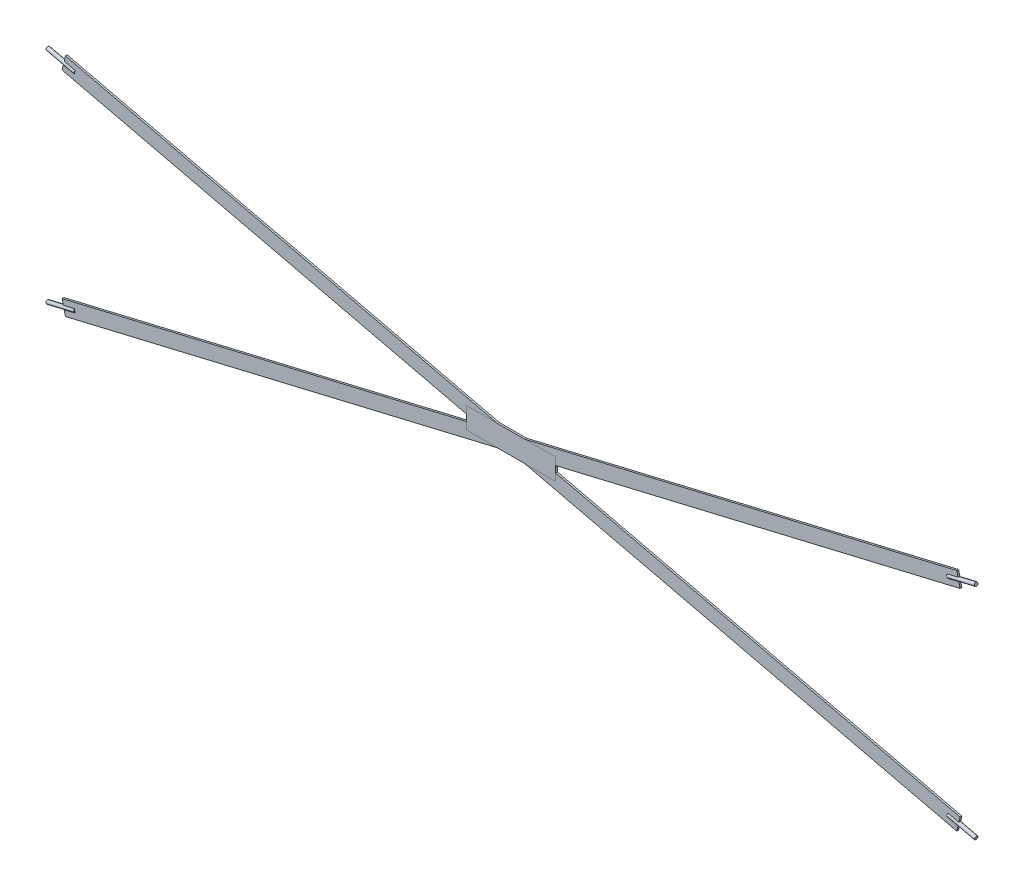
SolidWorks part; units mm, degrees
material "Plain Carbon Steel"
ref_plane "Front Plane" through (0, 0, 0) normal (0, 0, 1) x (1, 0, 0)
ref_plane "Top Plane" through (0, 0, 0) normal (0, 1, 0) x (1, 0, 0)
ref_plane "Right Plane" through (0, 0, 0) normal (1, 0, 0) x (0, 0, -1)
sketch "Sketch1" plane through (0, 0, 0) normal (0, 0, 1) x (1, 0, 0)
  line L0 (2522.0281, -597.1118) -> (-2522.0281, 597.1118)
  line L1 (-2522.0281, -597.1118) -> (2522.0281, 597.1118)
  line L2 (250, -59.1896) -> (-250, -59.1896)
  line L3 (250, -59.1896) -> (250, 59.1896)
  line L4 (250, 59.1896) -> (-250, 59.1896)
  line L5 (-250, -59.1896) -> (-250, 59.1896)
  line L6 (250, -59.1896) -> (-250, 59.1896) construction
  line L7 (250, 59.1896) -> (-250, -59.1896) construction
  line L8 (0, 0) -> (2683.4766, 0) construction
  point P2 (0, 0)
  point P5 (0, 0)
  dimension "D1" = 2591.75
  dimension "D2" = 2591.75
  dimension "D3" = 500
  dimension "D4" = 13.32
  dimension "D5" = 13.32
  dimension "D6" = 5183.5
  dimension "D7" = 5183.5
extrude "Boss-Extrude1" add sketch "Sketch1" along normal mid plane 10 contours L1 L4 L0 | L0 L3 L1 | L2 L0 L1 | L5 L1 L0
sketch "Sketch2" plane through (0, 0, 0) normal (0, 0, 1) x (1, 0, 0)
  line L0 (250, 18.0838) -> (250, 59.1896)
  line L1 (250, -59.1896) -> (250, 59.1896) construction
  line L2 (250, 59.1896) -> (76.3809, 59.1896)
  line L3 (250, 59.1896) -> (-250, 59.1896) construction
  line L4 (76.3809, 59.1896) -> (2496.4769, 632.1682)
  line L5 (250, 18.0838) -> (2514.9081, 554.3203)
  line L6 (-2522.0281, -597.1118) -> (2522.0281, 597.1118) construction
  line L7 (2514.9081, 554.3203) -> (2496.4769, 632.1682)
  line L8 (0, 59.1896) -> (0, 886.3837) construction
  line L9 (250, 59.1896) -> (-250, 59.1896) construction
  line L10 (-2514.9081, 554.3203) -> (-2496.4769, 632.1682)
  line L11 (-250, 18.0838) -> (-2514.9081, 554.3203)
  line L12 (-76.3809, 59.1896) -> (-2496.4769, 632.1682)
  line L13 (-250, 59.1896) -> (-76.3809, 59.1896)
  line L14 (-250, 18.0838) -> (-250, 59.1896)
  line L15 (11.5564, 0) -> (3168.9278, 0) construction
  line L16 (0, 0) -> (2683.4766, 0) construction
  line L17 (0, -59.1896) -> (0, -886.3837) construction
  line L18 (-250, -18.0838) -> (-250, -59.1896)
  line L19 (-250, -59.1896) -> (-76.3809, -59.1896)
  line L20 (-76.3809, -59.1896) -> (-2496.4769, -632.1682)
  line L21 (-250, -18.0838) -> (-2514.9081, -554.3203)
  line L22 (-2514.9081, -554.3203) -> (-2496.4769, -632.1682)
  line L23 (2514.9081, -554.3203) -> (2496.4769, -632.1682)
  line L24 (250, -18.0838) -> (2514.9081, -554.3203)
  line L25 (76.3809, -59.1896) -> (2496.4769, -632.1682)
  line L26 (250, -59.1896) -> (76.3809, -59.1896)
  line L27 (250, -18.0838) -> (250, -59.1896)
  point P17 (2505.6925, 593.2442)
  point P19 (-2505.6925, 593.2442)
  point P42 (-2505.6925, -593.2442)
  point P43 (2505.6925, -593.2442)
  dimension "D1" = 40
  dimension "D2" = 40
  dimension "D3" = 2487
extrude "Boss-Extrude2" add sketch "Sketch2" along normal mid plane 10 separate body
sketch "Sketch3" plane through (0, 0, 5) normal (0, 0, 1) x (1, 0, 0)
  line L0 (2602.1798, 605.812) -> (2446.4841, 568.9497)
  line L1 (2602.1798, 605.812) -> (2597.5721, 625.2739)
  line L2 (2446.4841, 568.9497) -> (2441.8763, 588.4116)
  line L3 (2597.5721, 625.2739) -> (2441.8763, 588.4116)
  line L4 (2602.1798, 605.812) -> (2441.8763, 588.4116) construction
  line L5 (2446.4841, 568.9497) -> (2597.5721, 625.2739) construction
  line L6 (2496.4769, 632.1682) -> (76.3809, 59.1896) construction
  point P1 (2522.0281, 597.1118)
  dimension "D1" = 20
  dimension "D2" = 160
extrude "Cut-Extrude1" cut sketch "Sketch3" against normal through all both and the other way through all
sketch "Sketch4" plane through (2444.1802, 578.6806, 0) normal (0.9731, 0.2304, 0) x (0, 0, -1)
  line L0 (-5, 10) -> (5, -10) construction
  circle A0 centre (0, 0) radius 10
  point P4 (0, 0)
  dimension "D1" = 20
extrude "Boss-Extrude4" add sketch "Sketch4" along normal blind 160 separate body
mirror "Mirror1" about plane through (0, 0, 0) normal (1, 0, 0) of "Cut-Extrude1"
mirror "Mirror2" about plane through (0, 0, 0) normal (0, 1, 0) of "Cut-Extrude1", "Mirror1"
mirror "Mirror3" about plane through (0, 0, 0) normal (1, 0, 0) of bodies 110 111
mirror "Mirror4" about plane through (0, 0, 0) normal (0, 1, 0) of bodies 110 112 111
